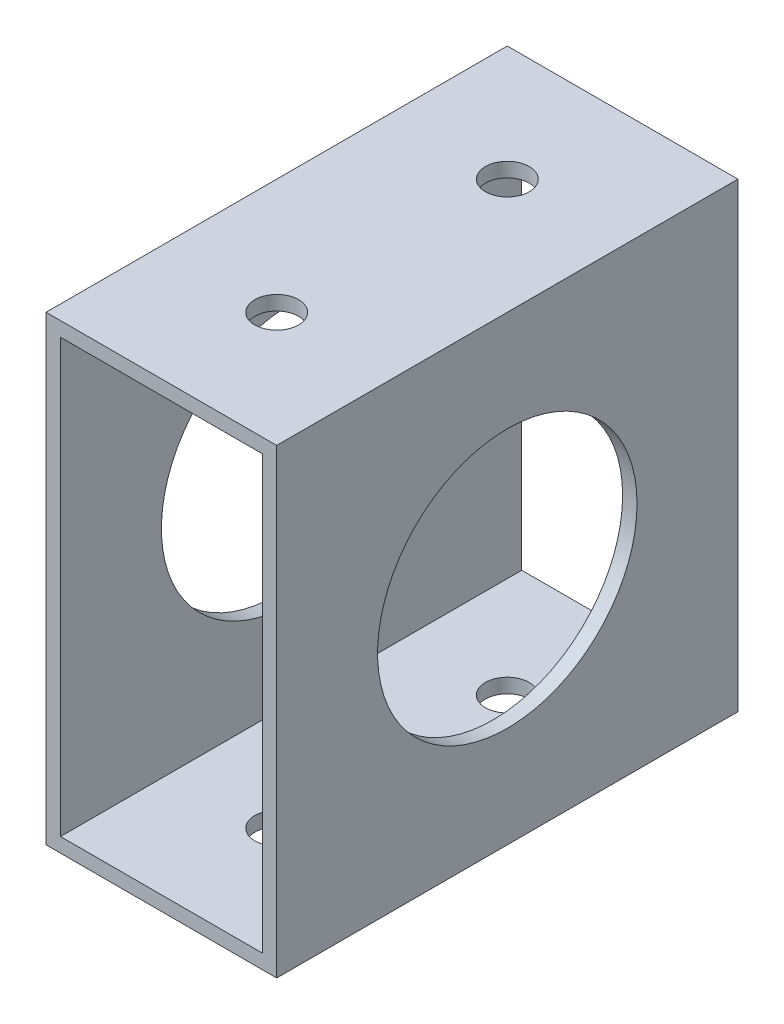
SolidWorks part; units mm, degrees
ref_plane "Front Plane" through (0, 0, 0) normal (0, 0, 1) x (1, 0, 0)
ref_plane "Top Plane" through (0, 0, 0) normal (0, 1, 0) x (1, 0, 0)
ref_plane "Right Plane" through (0, 0, 0) normal (1, 0, 0) x (0, 0, -1)
sketch "Sketch1" plane through (0, 0, 0) normal (0, 0, 1) x (1, 0, 0)
  line L1 (0, 0) -> (25.4, 0)
  line L2 (0, 0) -> (0, 50.8)
  line L3 (0, 50.8) -> (25.4, 50.8)
  line L4 (25.4, 0) -> (25.4, 50.8)
  line L5 (1.5875, 49.2125) -> (23.8125, 49.2125)
  line L6 (1.5875, 49.2125) -> (1.5875, 1.5875)
  line L7 (1.5875, 1.5875) -> (23.8125, 1.5875)
  line L8 (23.8125, 49.2125) -> (23.8125, 1.5875)
  dimension "D1" = 25.4
  dimension "D2" = 50.8
  dimension "D3" = 1.5875
  dimension "D4" = 1.5875
  dimension "D5" = 1.5875
  dimension "D6" = 1.5875
extrude "Boss-Extrude1" add sketch "Sketch1" along normal blind 50.8
sketch "Sketch2" plane through (0, 50.8, 0) normal (0, 1, 0) x (1, 0, 0)
  line L0 (25.4, 0) -> (0, 0) construction
  line L1 (0, -50.8) -> (0, 0) construction
  line L2 (25.4, -50.8) -> (0, -50.8) construction
  line L3 (25.4, -50.8) -> (25.4, 0) construction
  circle A1 centre (12.7, -12.7) radius 2.413
  circle A3 centre (12.7, -38.1) radius 2.413
  dimension "D2" = 4.826
  dimension "D4" = 4.826
  dimension "D7" = 12.7
  dimension "D8" = 12.7
  dimension "D10" = 12.7
  dimension "D12" = 12.7
extrude "Cut-Extrude1" cut sketch "Sketch2" against normal through all
sketch "Sketch3" plane through (25.4, 0, 0) normal (1, 0, 0) x (0, 0, -1)
  circle A0 centre (-25.4, 25.4) radius 14.2875
  dimension "D1" = 28.575
extrude "Cut-Extrude2" cut sketch "Sketch3" against normal through all
equation "\".19o\"=0.603901"
